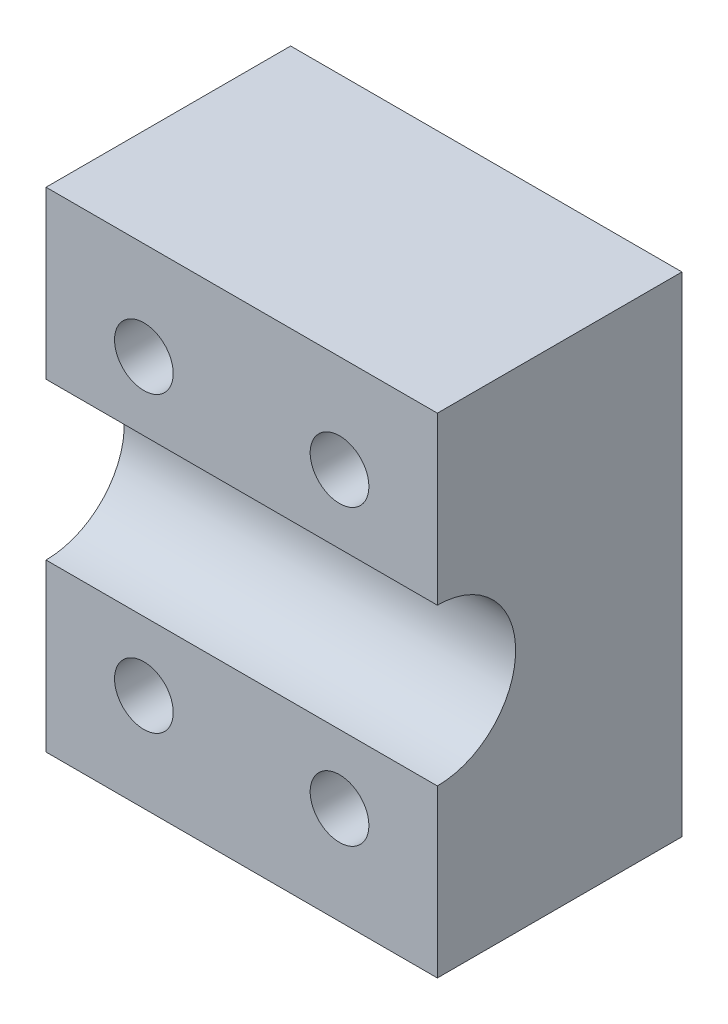
SolidWorks part; units mm, degrees
ref_plane "Front Plane" through (0, 0, 0) normal (0, 0, 1) x (1, 0, 0)
ref_plane "Top Plane" through (0, 0, 0) normal (0, 1, 0) x (1, 0, 0)
ref_plane "Right Plane" through (0, 0, 0) normal (1, 0, 0) x (0, 0, -1)
sketch "Sketch1" plane through (0, 0, 0) normal (0, 0, 1) x (1, 0, 0)
  line L1 (0, 0) -> (40, 0)
  line L2 (0, 0) -> (0, 50)
  line L3 (0, 50) -> (40, 50)
  line L4 (40, 0) -> (40, 50)
  dimension "D1" = 50
  dimension "D2" = 40
extrude "Boss-Extrude1" add sketch "Sketch1" along normal blind 25
sketch "Sketch2" plane through (0, 0, 0) normal (-1, 0, 0) x (0, 0, 1)
  line L0 (25, 50) -> (25, 0) construction
  circle A0 centre (25, 25) radius 8
  dimension "D1" = 16
extrude "Cut-Extrude1" cut sketch "Sketch2" against normal blind 58
sketch "Sketch3" plane through (0, 0, 25) normal (0, 0, 1) x (1, 0, 0)
  line L0 (40, 50) -> (0, 50) construction
  line L1 (40, 33) -> (40, 50) construction
  line L3 (0, 50) -> (0, 33) construction
  line L4 (0, 0) -> (40, 0) construction
  line L5 (0, 17) -> (0, 0) construction
  line L6 (40, 0) -> (40, 17) construction
  circle A0 centre (10, 40) radius 3
  circle A1 centre (30, 40) radius 3
  circle A2 centre (30, 10) radius 3
  circle A3 centre (10, 10) radius 3
  point P18 (0, 8.5)
  dimension "D1" = 10
  dimension "D2" = 10
  dimension "D3" = 10
  dimension "D4" = 10
  dimension "D5" = 6
  dimension "D6" = 6
  dimension "D7" = 6
  dimension "D8" = 6
  dimension "D9" = 10
  dimension "D10" = 10
  dimension "D11" = 10
  dimension "D12" = 10
extrude "Cut-Extrude2" cut sketch "Sketch3" against normal blind 25
